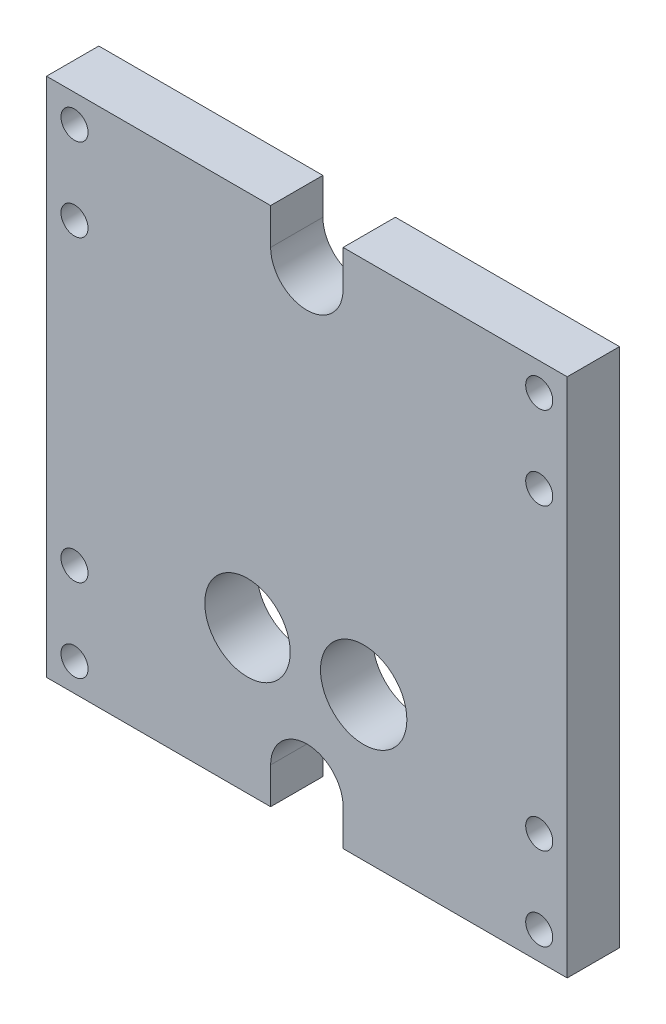
SolidWorks part; units mm, degrees
ref_plane "Front Plane" through (0, 0, 0) normal (0, 0, 1) x (1, 0, 0)
ref_plane "Top Plane" through (0, 0, 0) normal (0, 1, 0) x (1, 0, 0)
ref_plane "Right Plane" through (0, 0, 0) normal (1, 0, 0) x (0, 0, -1)
sketch "Sketch3" plane through (0, 0, 0) normal (0, 0, 1) x (1, 0, 0)
  line L1 (-49.5558, -49.6889) -> (50.0442, -49.6889)
  line L2 (-49.5558, -49.6889) -> (-49.5558, 49.9111)
  line L3 (-49.5558, 49.9111) -> (50.0442, 49.9111)
  line L4 (50.0442, -49.6889) -> (50.0442, 49.9111)
  line L5 (7.1792, -35.8189) -> (-6.6908, -35.8189)
  line L6 (7.1792, -35.8189) -> (7.1792, -49.6889)
  line L7 (7.1792, -49.6889) -> (-6.6908, -49.6889)
  line L8 (-6.6908, -35.8189) -> (-6.6908, -49.6889)
  line L9 (7.1792, -35.8189) -> (-6.6908, -49.6889) construction
  line L10 (7.1792, -49.6889) -> (-6.6908, -35.8189) construction
  line L11 (7.1792, 36.0411) -> (-6.6908, 36.0411)
  line L12 (7.1792, 36.0411) -> (7.1792, 49.9111)
  line L13 (7.1792, 49.9111) -> (-6.6908, 49.9111)
  line L14 (-6.6908, 36.0411) -> (-6.6908, 49.9111)
  line L15 (7.1792, 36.0411) -> (-6.6908, 49.9111) construction
  line L16 (7.1792, 49.9111) -> (-6.6908, 36.0411) construction
  circle A0 centre (-11.1125, -22.225) radius 8.1723
  circle A1 centre (11.1125, -22.225) radius 8.2632
  circle A2 centre (0.2442, -42.7539) radius 6.935
  circle A3 centre (0.2442, 42.9761) radius 6.935
extrude "Boss-Extrude4" add sketch "Sketch3" along normal blind 10 contours L11 L14 L3 L2 L1 L8 L5 L6 L4 L12 A1 A0 | A2 L5 L8 | A2 L6 L5 | A3 L14 L11 | A3 L11 L12
hole_wizard "#6 (0.204) Diameter Hole1" positions "Sketch4" profile "Sketch5" hole size "#6" standard "ANSI Inch" end condition through all
sketch "Sketch4" plane through (0, 0, 0) normal (0, 0, -1) x (-1, 0, 0)
  point P0 (44.2058, -44.3389)
  point P3 (-44.6942, -44.3389)
  point P6 (-44.6942, 44.5611)
  point P9 (44.2058, 44.5611)
  point P12 (44.2058, 28.6861)
  point P15 (44.2058, -28.4639)
  point P18 (-44.6942, -28.4639)
  point P21 (-44.6942, 28.6861)
sketch "Sketch5" plane through (-44.2058, -44.3389, 0) normal (1, 0, 0) x (0, 1, 0)
  line L0 (0, 0) -> (0, 10)
  line L1 (0, 10) -> (2.5908, 10)
  line L2 (2.5908, 10) -> (2.5908, 0)
  line L5 (2.5908, 0) -> (0, 0)
  line L11 (0, -6.35) -> (0, 107.95) construction
  dimension "Thru Hole Dia." = 5.1816
  dimension "Thru Hole Depth" = 10
